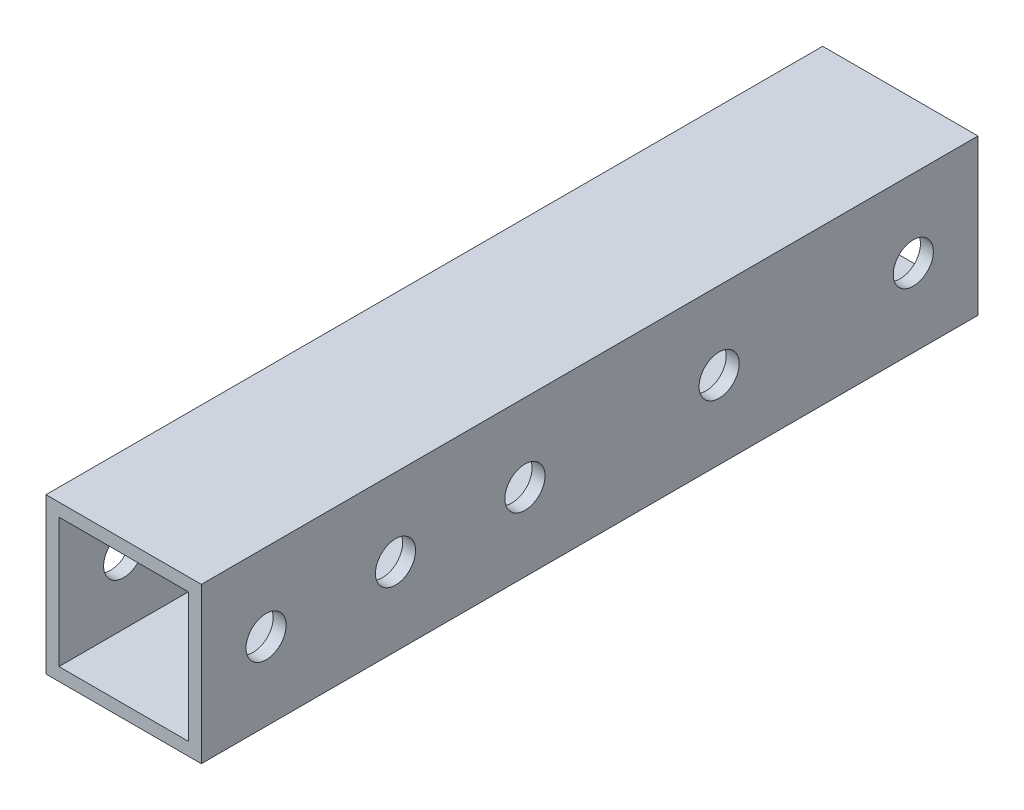
SolidWorks part; units mm, degrees
material "Thornel Mat VMA"
ref_plane "前视基准面" through (0, 0, 0) normal (0, 0, 1) x (1, 0, 0)
ref_plane "上视基准面" through (0, 0, 0) normal (0, 1, 0) x (1, 0, 0)
ref_plane "右视基准面" through (0, 0, 0) normal (1, 0, 0) x (0, 0, -1)
other "Configuration Table"
sketch "草图1" plane through (0, 0, 0) normal (0, 0, 1) x (1, 0, 0)
  line L0 (1, 1) -> (1, 11)
  line L1 (0, 0) -> (12, 0)
  line L2 (0, 0) -> (0, 12)
  line L3 (0, 12) -> (12, 12)
  line L4 (12, 0) -> (12, 12)
  line L5 (1, 11) -> (11, 11)
  line L6 (11, 1) -> (11, 11)
  line L7 (1, 1) -> (11, 1)
  dimension "D1" = 12
  dimension "D2" = 12
  dimension "D3" = 1
extrude "凸台-拉伸1" add sketch "草图1" along normal blind 60
sketch "草图2" plane through (12, 0, 0) normal (1, 0, 0) x (0, 1, 0)
  line L0 (6, 60) -> (6, 0) construction
  line L1 (0, 60) -> (12, 60) construction
  line L2 (0, 0) -> (12, 0) construction
  circle A1 centre (6, 55) radius 1.55
  circle A7 centre (6, 45) radius 1.55
  circle A8 centre (6, 5) radius 1.55
  circle A9 centre (6, 20) radius 1.55
  circle A10 centre (6, 35) radius 1.55
  dimension "D1" = 3.1
  dimension "D2" = 3.1
  dimension "D5" = 3.1
  dimension "D4" = 3.1
  dimension "D6" = 3.1
  dimension "D3" = 5
  dimension "D7" = 10
  dimension "D8" = 5
  dimension "D9" = 15
  dimension "D10" = 15
extrude "切除-拉伸2" cut sketch "草图2" against normal through all
